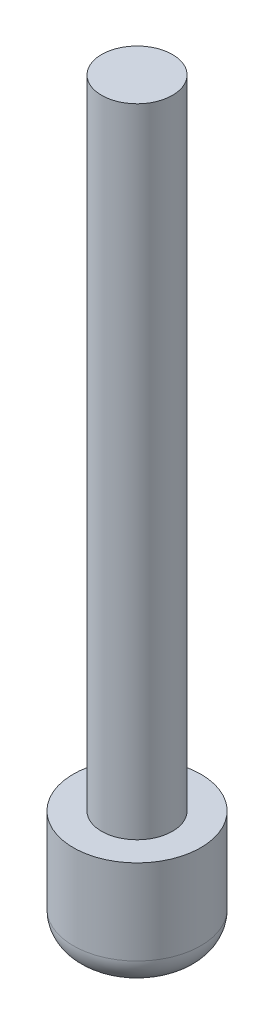
SolidWorks part; units mm, degrees
ref_plane "Front Plane" through (0, 0, 0) normal (0, 0, 1) x (1, 0, 0)
ref_plane "Top Plane" through (0, 0, 0) normal (0, 1, 0) x (1, 0, 0)
ref_plane "Right Plane" through (0, 0, 0) normal (1, 0, 0) x (0, 0, -1)
sketch "Sketch1" plane through (0, 0, 0) normal (0, 1, 0) x (1, 0, 0)
  circle A0 centre (0, 0.1662) radius 1.25
  dimension "D1" = 2.5
extrude "Boss-Extrude1" add sketch "Sketch1" along normal blind 22.5
sketch "Sketch2" plane through (0, 0, 0) normal (0, -1, 0) x (-1, 0, 0)
  circle A0 centre (0, 0.1662) radius 2.25
  dimension "D1" = 4.5
extrude "Boss-Extrude2" add sketch "Sketch2" along normal blind 4
fillet "Fillet1" radius 1 1 edges at (0, -4, -2.4162)
